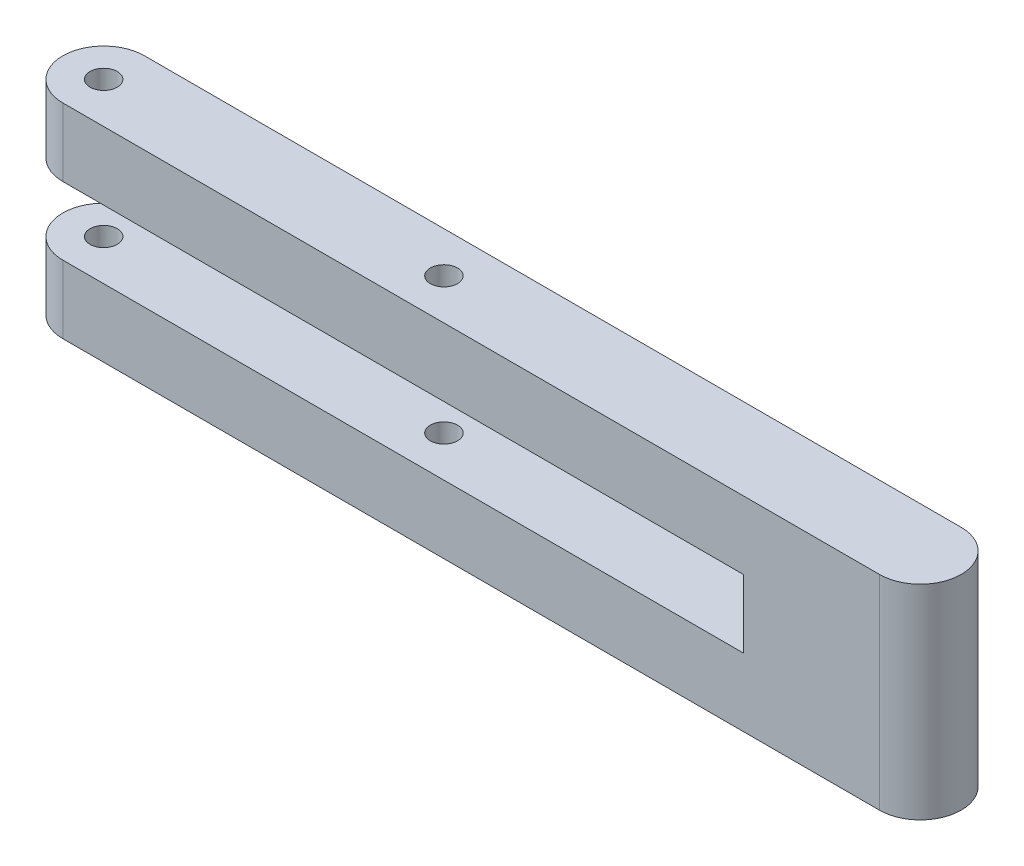
SolidWorks part; units mm, degrees
ref_plane "Front Plane" through (0, 0, 0) normal (0, 0, 1) x (1, 0, 0)
ref_plane "Top Plane" through (0, 0, 0) normal (0, 1, 0) x (1, 0, 0)
ref_plane "Right Plane" through (0, 0, 0) normal (1, 0, 0) x (0, 0, -1)
sketch "Sketch3" plane through (0, 0, 0) normal (0, 1, 0) x (1, 0, 0)
  line L0 (-63.5, 0) -> (88.9, 0) construction
  line L1 (-20.955, 0) -> (20.955, 0) construction
  line L2 (-63.5, 7.62) -> (88.9, 7.62)
  line L3 (-63.5, -7.62) -> (88.9, -7.62)
  arc A0 (-63.5, 7.62) -> (-63.5, -7.62) centre (-63.5, 0) ccw
  arc A1 (88.9, -7.62) -> (88.9, 7.62) centre (88.9, 0) ccw
  point P5 (12.7, 0)
  dimension "D2" = 7.62
  dimension "D1" = 152.4
  dimension "D3" = 63.5
extrude "Boss-Extrude1" add sketch "Sketch3" along normal blind 38.1
sketch "Sketch4" plane through (0, 38.1, 0) normal (0, 1, 0) x (1, 0, 0)
  circle A0 centre (-63.5, 0) radius 2.54
  circle A1 centre (0, 0) radius 2.54
  dimension "D3" = 63.5
  dimension "D1" = 5.08
  dimension "D2" = 2
extrude "Cut-Extrude3" cut sketch "Sketch4" against normal through all
ref_plane "Plane2" through (0, 19.05, 0) normal (0, 1, 0) x (1, 0, 0)
sketch "Sketch5" plane through (0, 19.05, 0) normal (0, 1, 0) x (1, 0, 0)
  line L0 (0, -8.382) -> (0, 8.382) construction
  line L1 (-63.5, 7.62) -> (31.75, 7.62)
  line L2 (-63.5, -7.62) -> (0, -7.62)
  line L3 (-63.5, -7.62) -> (88.9, -7.62) construction
  line L4 (31.75, 7.62) -> (63.5, 7.62)
  line L6 (0, -7.62) -> (63.5, -7.62)
  line L7 (63.5, 7.62) -> (63.5, -7.62)
  arc A0 (-63.5, 7.62) -> (-63.5, -7.62) centre (-63.5, 0) ccw
  point P4 (-7.62, 0)
  point P9 (0, 0)
  dimension "D3" = 63.5
  dimension "D1" = 7.62
  dimension "D2" = 127
  dimension "D4" = 15.24
  dimension "D5" = 63.5
  dimension "D6" = 7.62
  dimension "D7" = 7.62
  dimension "D8" = 31.75
extrude "Cut-Extrude4" cut sketch "Sketch5" against normal blind 6.35 and the other way blind 6.35
equation "\"TibiaLength\"= 5in"
equation "\"TibiaRadius\"= 0.3in"
equation "\"TibiaDistFromCentre\"= \"TibiaLength\" / 2"
equation "\"TibiaThickness\"= 0.5in"
equation "\"HoleRadius\"= 0.2in"
equation "\"D1@Sketch3\"= \"TibiaLength\" * 1.2"
equation "\"D2@Sketch3\"= \"TibiaRadius\""
equation "\"D3@Sketch3\"= \"TibiaDistFromCentre\""
equation "\"D1@Boss-Extrude1\"=\"TibiaThickness\"*3"
equation "\"D1@Sketch4\"= \"HoleRadius\""
equation "\"D2@Sketch5\"=\"TibiaLength\""
equation "\"D3@Sketch5\"=\"TibiaDistFromCentre\""
equation "\"D4@Sketch5\"=\"TibiaRadius\"*2"
equation "\"D5@Sketch5\"=\"TibiaDistFromCentre\""
equation "\"D7@Sketch5\"=\"TibiaRadius\""
equation "\"D8@Sketch5\"=\"TibiaDistFromCentre\"/2"
equation "\"D1@Sketch5\"=\"TibiaRadius\""
equation "\"D6@Sketch5\"=\"TibiaRadius\""
equation "\"D1@Cut-Extrude4\"= \"TibiaThickness\" * 0.5"
equation "\"D2@Cut-Extrude4\"= \"TibiaThickness\" * 0.5"
equation "\"D3@Sketch4\"=\"TibiaLength\"*0.5"
